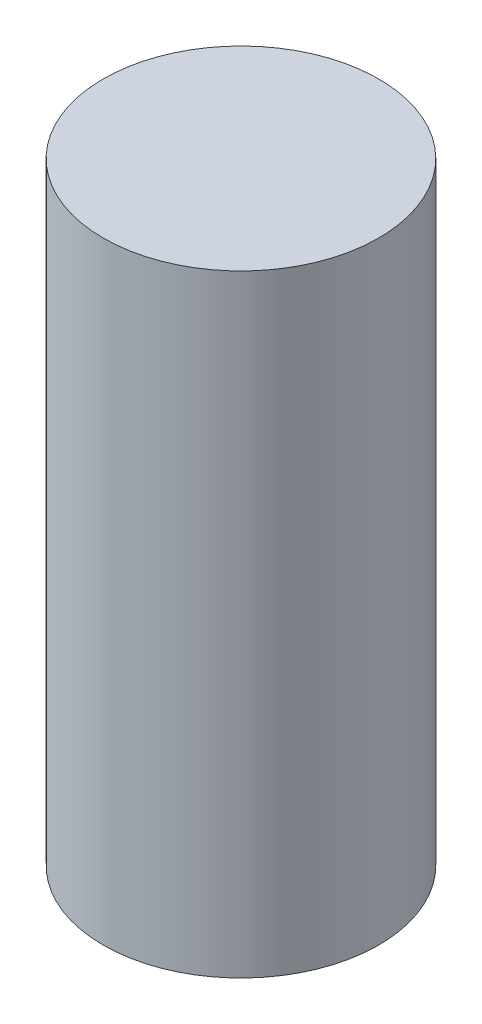
SolidWorks part; units mm, degrees
ref_plane "Front Plane" through (0, 0, 0) normal (0, 0, 1) x (1, 0, 0)
ref_plane "Top Plane" through (0, 0, 0) normal (0, 1, 0) x (1, 0, 0)
ref_plane "Right Plane" through (0, 0, 0) normal (1, 0, 0) x (0, 0, -1)
sketch "Sketch2" plane through (0, 0, 0) normal (0, 1, 0) x (1, 0, 0)
  circle A0 centre (-2.7192, 2.472) radius 4.5
extrude "Boss-Extrude1" add sketch "Sketch2" along normal blind 20
